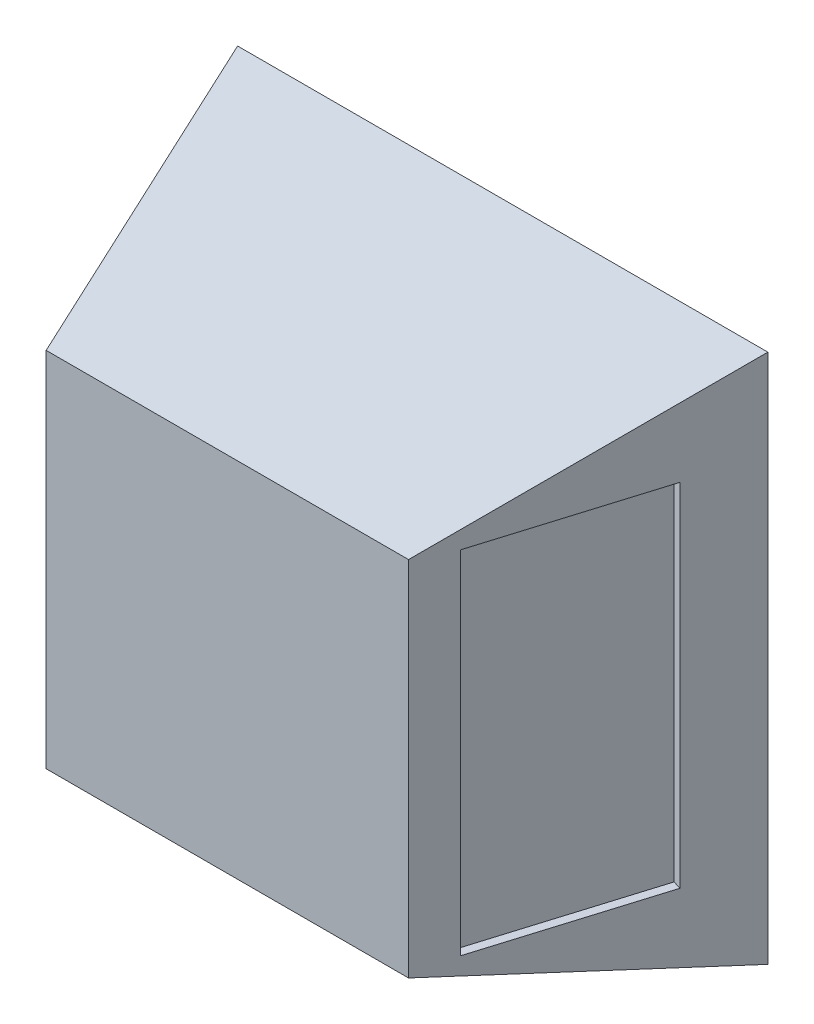
SolidWorks part; units mm, degrees
ref_plane "Front Plane" through (0, 0, 0) normal (0, 0, 1) x (1, 0, 0)
ref_plane "Top Plane" through (0, 0, 0) normal (0, 1, 0) x (1, 0, 0)
ref_plane "Right Plane" through (0, 0, 0) normal (1, 0, 0) x (0, 0, -1)
sketch "Sketch1" plane through (0, 0, 0) normal (0, 0, 1) x (1, 0, 0)
  line L1 (-9.05, 9.05) -> (9.05, 9.05)
  line L2 (-9.05, 9.05) -> (-9.05, -9.05)
  line L3 (-9.05, -9.05) -> (9.05, -9.05)
  line L4 (9.05, 9.05) -> (9.05, -9.05)
  line L5 (0, -9.05) -> (0, 9.05) construction
  line L6 (-9.05, 0) -> (9.05, 0) construction
  line L7 (-7.05, 7.05) -> (7.05, 7.05) construction
  line L8 (-7.05, 7.05) -> (-7.05, -7.05) construction
  line L9 (-7.05, -7.05) -> (7.05, -7.05) construction
  line L10 (7.05, 7.05) -> (7.05, -7.05) construction
  line L11 (0, -7.05) -> (0, 7.05) construction
  line L12 (-7.05, 0) -> (7.05, 0) construction
  point P0 (0, 0)
  point P4 (0, 0)
  dimension "D1" = 18.1
  dimension "D2" = 18.1
  dimension "D3" = 2
  dimension "D4" = 2
ref_plane "Plane1" through (0, 0, 9.4) normal (0, 0, 1) x (1, 0, 0)
sketch "Sketch2" plane through (0, 0, 9.4) normal (0, 0, 1) x (1, 0, 0)
  line L1 (-6.185, 6.185) -> (6.185, 6.185)
  line L2 (-6.185, 6.185) -> (-6.185, -6.185)
  line L3 (-6.185, -6.185) -> (6.185, -6.185)
  line L4 (6.185, 6.185) -> (6.185, -6.185)
  line L5 (0, -6.185) -> (0, 6.185) construction
  line L6 (-6.185, 0) -> (6.185, 0) construction
  line L7 (-4.585, 4.585) -> (4.585, 4.585) construction
  line L8 (-4.585, 4.585) -> (-4.585, -4.585) construction
  line L9 (-4.585, -4.585) -> (4.585, -4.585) construction
  line L10 (4.585, 4.585) -> (4.585, -4.585) construction
  line L11 (0, -4.585) -> (0, 4.585) construction
  line L12 (-4.585, 0) -> (4.585, 0) construction
  point P0 (0, 0)
  point P4 (0, 0)
  dimension "D1" = 12.37
  dimension "D2" = 12.37
  dimension "D3" = 1.6
  dimension "D4" = 1.6
loft "Loft2" add profiles "Sketch1", "Sketch2"
sketch "Sketch4" plane through (0, 0, 0) normal (0, 1, 0) x (1, 0, 0)
  line L0 (-6.185, -9.4) -> (6.185, -9.4)
  line L1 (-9.9551, -9.4) -> (9.9551, -9.4) construction
  line L2 (9.05, 0) -> (6.185, -9.4) construction
  line L3 (-9.05, 0) -> (-6.185, -9.4) construction
  spline S0 degree 2 poles (-6.185, -9.4) (0, -7.8931) (6.185, -9.4) knots 0 0 0 1 1 1
shell "Shell4" thickness 2.5
ref_plane "Plane2" through (0, 0, -4) normal (0, 0, 1) x (1, 0, 0)
sketch "Sketch5" plane through (0, 0, -4) normal (0, 0, 1) x (1, 0, 0)
  line L1 (-2.9, 2) -> (2.9, 2)
  line L2 (-2.9, 2) -> (-2.9, -2)
  line L3 (-2.9, -2) -> (2.9, -2)
  line L4 (2.9, 2) -> (2.9, -2)
  line L5 (0, -2) -> (0, 2) construction
  line L6 (-2.9, 0) -> (2.9, 0) construction
  point P0 (0, 0)
  dimension "D1" = 5.8
  dimension "D2" = 4
extrude "Boss-Extrude1" add sketch "Sketch5" along normal up to surface (10.9 mm away) up to face at (0, 0, 6.9)
sketch "Sketch6" plane through (0, 0, -4) normal (0, 0, -1) x (-1, 0, 0)
  line L0 (0, -2.15) -> (0, 2.15) construction
  line L1 (2.15, 0) -> (-2.15, 0) construction
  line L2 (0.73, 2.15) -> (-0.73, 2.15)
  line L3 (-0.73, 2.15) -> (-0.73, 0.73)
  line L4 (-0.73, 0.73) -> (-2.15, 0.73)
  line L5 (-2.15, 0.73) -> (-2.15, -0.73)
  line L6 (-0.73, -0.73) -> (-2.15, -0.73)
  line L7 (-0.73, -2.15) -> (-0.73, -0.73)
  line L8 (0.73, -2.15) -> (-0.73, -2.15)
  line L9 (0.73, -2.15) -> (0.73, -0.73)
  line L10 (0.73, -0.73) -> (2.15, -0.73)
  line L11 (2.15, 0.73) -> (2.15, -0.73)
  line L12 (0.73, 0.73) -> (2.15, 0.73)
  line L13 (0.73, 2.15) -> (0.73, 0.73)
  point P12 (0, 0)
  dimension "D1" = 2.15
  dimension "D2" = 2.15
  dimension "D3" = 0.73
  dimension "D4" = 0.73
extrude "Cut-Extrude3" cut sketch "Sketch6" against normal blind 4
sketch "Sketch7" plane through (8.2808, 0, 2.5239) normal (-0.9566, 0, -0.2915) x (0, -1, 0)
  line L0 (0, 2.7658) -> (0, 0) construction
  line L1 (-6, 5.7658) -> (6, 5.7658)
  line L2 (-6, 5.7658) -> (-6, -0.2342)
  line L3 (-6, -0.2342) -> (6, -0.2342)
  line L4 (6, 5.7658) -> (6, -0.2342)
  line L5 (-6, 5.7658) -> (6, -0.2342) construction
  line L6 (-6, -0.2342) -> (6, 5.7658) construction
  point P4 (0, 2.7658)
  dimension "D1" = 12
  dimension "D2" = 6
extrude "Cut-Extrude4" cut sketch "Sketch7" along normal blind 0.3
